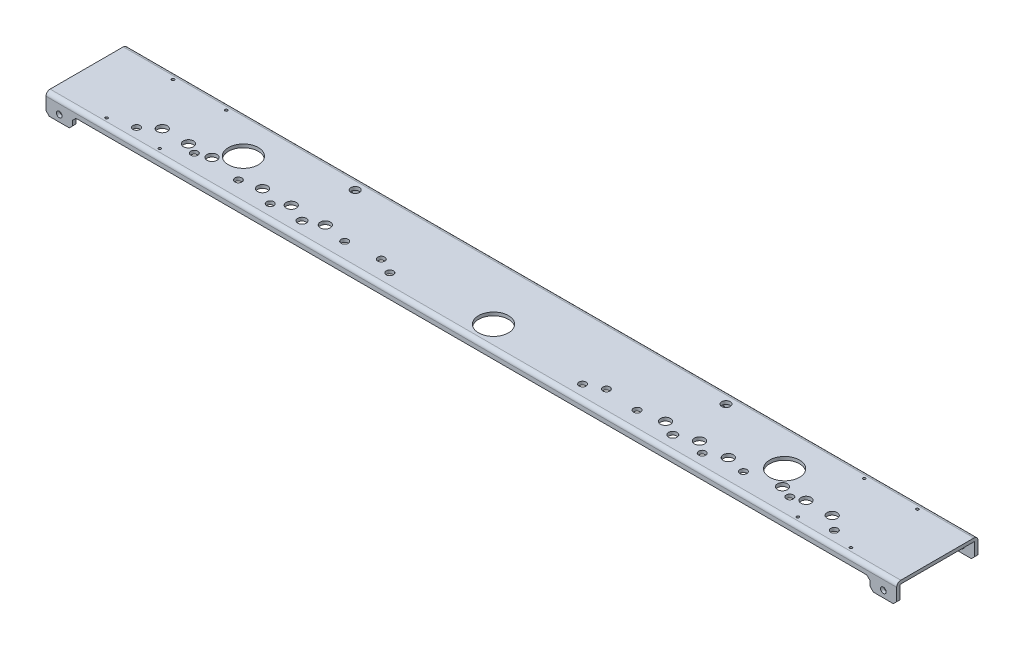
SolidWorks part; units mm, degrees
material "6061-T6 (SS)"
ref_plane "Front Plane" through (0, 0, 0) normal (0, 0, 1) x (1, 0, 0)
ref_plane "Top Plane" through (0, 0, 0) normal (0, 1, 0) x (1, 0, 0)
ref_plane "Right Plane" through (0, 0, 0) normal (1, 0, 0) x (0, 0, -1)
ref_plane "Plane1" through (0, -15.875, 0) normal (0, -1, 0) x (1, 0, 0)
sketch "Sketch1" plane through (0, -15.875, 0) normal (0, -1, 0) x (1, 0, 0)
  line L0 (812.8, 3.937) -> (0, 3.937)
  line L1 (0, 3.937) -> (0, -73.787)
  line L2 (0, -73.787) -> (812.8, -73.787)
  line L3 (812.8, -73.787) -> (812.8, 3.937)
extrude "Boss-Extrude1" add sketch "Sketch1" against normal blind 19.05
sketch "Sketch2" plane through (0, 0, 0) normal (-1, 0, 0) x (0, 0, 1)
  line L0 (-70.612, -15.875) -> (0.762, -15.875)
  line L1 (0.762, -15.875) -> (0.762, 0)
  line L2 (0.762, 0) -> (-70.612, 0)
  line L3 (-70.612, 0) -> (-70.612, -15.875)
extrude "Cut-Extrude1" cut sketch "Sketch2" against normal through all
sketch "Sketch3" plane through (0, 0, 3.937) normal (0, 0, 1) x (1, 0, 0)
  line L0 (787.4, -15.875) -> (787.4, -4.7625)
  line L1 (787.4, -4.7625) -> (25.4, -4.7625)
  line L2 (25.4, -4.7625) -> (25.4, -15.875)
  line L3 (25.4, -15.875) -> (787.4, -15.875)
extrude "Cut-Extrude2" cut sketch "Sketch3" against normal up to next
hole_wizard "M8 Clearance Hole1" positions "Sketch5" profile "Sketch4" hole size "M8" standard "ANSI Metric"
sketch "Sketch5" plane through (0, 3.175, 0) normal (0, 1, 0) x (1, 0, 0)
  point P0 (568.9249, 19.05)
  point P1 (601.4385, 19.05)
  point P2 (628.9477, 19.05)
  point P3 (243.8751, 19.05)
  point P4 (211.3615, 19.05)
  point P5 (183.8523, 19.05)
  point P6 (678.9442, 20.828)
  point P7 (701.4504, 20.828)
  point P8 (726.4609, 20.828)
  point P9 (133.8558, 20.828)
  point P10 (111.3496, 20.828)
  point P11 (86.3391, 20.828)
sketch "Sketch4" plane through (568.9249, 3.175, -19.05) normal (1, 0, 0) x (0, 0, 1)
  line L0 (0, 0) -> (0, 19.05)
  line L1 (0, 19.05) -> (4.826, 19.05)
  line L2 (4.826, 19.05) -> (4.826, 0)
  line L5 (4.826, 0) -> (0, 0)
  line L11 (0, -6.35) -> (0, 107.95) construction
  dimension "Thru Hole Dia." = 9.652
  dimension "Thru Hole Depth" = 19.05
hole_wizard "M2 Clearance Hole1" positions "Sketch7" profile "Sketch6" hole size "M2" standard "ANSI Metric"
sketch "Sketch7" plane through (0, 3.175, 0) normal (0, 1, 0) x (1, 0, 0)
  point P0 (711.2, 3.175)
  point P1 (711.2, 66.675)
  point P2 (762, 3.175)
  point P3 (762, 66.675)
  point P4 (101.6, 3.175)
  point P5 (50.8, 3.175)
  point P6 (101.6, 66.675)
  point P7 (50.8, 66.675)
sketch "Sketch6" plane through (711.2, 3.175, -3.175) normal (1, 0, 0) x (0, 0, 1)
  line L0 (0, 0) -> (0, 19.05)
  line L1 (0, 19.05) -> (1.27, 19.05)
  line L2 (1.27, 19.05) -> (1.27, 0)
  line L5 (1.27, 0) -> (0, 0)
  line L11 (0, -6.35) -> (0, 107.95) construction
  dimension "Thru Hole Dia." = 2.54
  dimension "Thru Hole Depth" = 19.05
hole_wizard "M25 Clearance Hole1" positions "Sketch9" profile "Sketch8" hole size "M25" standard "ANSI Metric"
sketch "Sketch9" plane through (0, 3.175, 0) normal (0, 1, 0) x (1, 0, 0)
  point P0 (664.9708, 36.83)
  point P1 (147.8292, 36.83)
  point P2 (406.4, 17.272)
sketch "Sketch8" plane through (664.9708, 3.175, -36.83) normal (1, 0, 0) x (0, 0, 1)
  line L0 (0, 0) -> (0, 19.05)
  line L1 (0, 19.05) -> (14.2875, 19.05)
  line L2 (14.2875, 19.05) -> (14.2875, 0)
  line L5 (14.2875, 0) -> (0, 0)
  line L11 (0, -6.35) -> (0, 107.95) construction
  dimension "Thru Hole Dia." = 28.575
  dimension "Thru Hole Depth" = 19.05
hole_wizard "M6 Clearance Hole1" positions "Sketch11" profile "Sketch10" hole size "M6" standard "ANSI Metric"
sketch "Sketch11" plane through (0, 3.175, 0) normal (0, 1, 0) x (1, 0, 0)
  point P0 (612.775, 10.287)
  point P1 (498.475, 10.287)
  point P2 (314.325, 10.287)
  point P3 (200.025, 10.287)
  point P4 (739.775, 9.525)
  point P5 (690.88, 15.875)
  point P6 (121.92, 15.875)
  point P7 (73.025, 9.525)
  point P8 (647.7, 14.732)
  point P9 (546.1, 14.732)
  point P10 (165.1, 14.732)
  point P11 (266.7, 14.732)
  point P12 (513.9255, 17.5473)
  point P13 (298.8745, 17.5473)
sketch "Sketch10" plane through (612.775, 3.175, -10.287) normal (1, 0, 0) x (0, 0, 1)
  line L0 (0, 0) -> (0, 19.05)
  line L1 (0, 19.05) -> (3.3782, 19.05)
  line L2 (3.3782, 19.05) -> (3.3782, 0)
  line L5 (3.3782, 0) -> (0, 0)
  line L11 (0, -6.35) -> (0, 107.95) construction
  dimension "Thru Hole Dia." = 6.7564
  dimension "Thru Hole Depth" = 19.05
hole_wizard "Hole1" positions "Sketch13" profile "Sketch12" legacy
sketch "Sketch13" plane through (0, 3.175, 0) normal (0, 1, 0) x (1, 0, 0)
  point P0 (583.5384, 62.23)
  point P1 (583.5384, 11.43)
  point P2 (229.2616, 11.43)
  point P3 (229.2616, 62.23)
sketch "Sketch12" plane through (583.5384, 3.175, -62.23) normal (1, 0, 0) x (0, 0, 1)
  line L0 (0, 0) -> (0, 19.05)
  line L1 (0, 19.05) -> (4.064, 19.05)
  line L2 (4.064, 19.05) -> (4.064, 0)
  line L3 (4.064, 0) -> (0, 0)
  line L4 (0, 110) -> (0, -10) construction
  dimension "Diameter" = 8.128
  dimension "Depth" = 19.05
hole_wizard "M5 Clearance Hole1" positions "Sketch15" profile "Sketch14" hole size "M5" standard "ANSI Metric"
sketch "Sketch15" plane through (0, 0, 0.762) normal (0, 0, -1) x (-1, 0, 0)
  point P0 (-12.7, -9.525)
  point P1 (-800.1, -9.525)
sketch "Sketch14" plane through (12.7, -9.525, 0.762) normal (1, 0, 0) x (0, 1, 0)
  line L0 (0, 0) -> (0, 3.175)
  line L1 (0, 3.175) -> (2.667, 3.175)
  line L2 (2.667, 3.175) -> (2.667, 0)
  line L5 (2.667, 0) -> (0, 0)
  line L11 (0, -6.35) -> (0, 107.95) construction
  dimension "Thru Hole Dia." = 5.334
  dimension "Thru Hole Depth" = 3.175
hole_wizard "M5 Clearance Hole2" positions "Sketch17" profile "Sketch16" hole size "M5" standard "ANSI Metric"
sketch "Sketch17" plane through (0, 0, -73.787) normal (0, 0, -1) x (-1, 0, 0)
  point P0 (-800.1, -9.525)
  point P1 (-774.7, -9.525)
  point P2 (-749.3, -9.525)
  point P3 (-723.9, -9.525)
  point P4 (-698.5, -9.525)
  point P5 (-673.1, -9.525)
  point P6 (-647.7, -9.525)
  point P7 (-622.3, -9.525)
  point P8 (-596.9, -9.525)
  point P9 (-571.5, -9.525)
  point P10 (-546.1, -9.525)
  point P11 (-520.7, -9.525)
  point P12 (-495.3, -9.525)
  point P13 (-469.9, -9.525)
  point P14 (-444.5, -9.525)
  point P15 (-419.1, -9.525)
  point P16 (-393.7, -9.525)
  point P17 (-368.3, -9.525)
  point P18 (-342.9, -9.525)
  point P19 (-317.5, -9.525)
  point P20 (-292.1, -9.525)
  point P21 (-266.7, -9.525)
  point P22 (-241.3, -9.525)
  point P23 (-215.9, -9.525)
  point P24 (-190.5, -9.525)
  point P25 (-165.1, -9.525)
  point P26 (-139.7, -9.525)
  point P27 (-114.3, -9.525)
  point P28 (-88.9, -9.525)
  point P29 (-63.5, -9.525)
  point P30 (-38.1, -9.525)
  point P31 (-12.7, -9.525)
sketch "Sketch16" plane through (800.1, -9.525, -73.787) normal (1, 0, 0) x (0, 1, 0)
  line L0 (0, 0) -> (0, 77.724)
  line L1 (0, 77.724) -> (2.667, 77.724)
  line L2 (2.667, 77.724) -> (2.667, 0)
  line L5 (2.667, 0) -> (0, 0)
  line L11 (0, -6.35) -> (0, 107.95) construction
  dimension "Thru Hole Dia." = 5.334
  dimension "Thru Hole Depth" = 77.724
chamfer "Chamfer1" distance 3.175 angle 45 8 edges at (25.4, -4.7625, 2.3495) (787.4, -4.7625, 2.3495) (0, -15.875, 2.3495) (25.4, -15.875, 2.3495) (812.8, -15.875, -72.1995) (812.8, -15.875, 2.3495) (0, -15.875, -72.1995) (787.4, -15.875, 2.3495)
fillet "Fillet1" radius 0.762 2 edges at (406.4, 0, -70.612) (406.4, 0, 0.762)
fillet "Fillet2" radius 3.937 2 edges at (406.4, 3.175, 3.937) (406.4, 3.175, -73.787)
